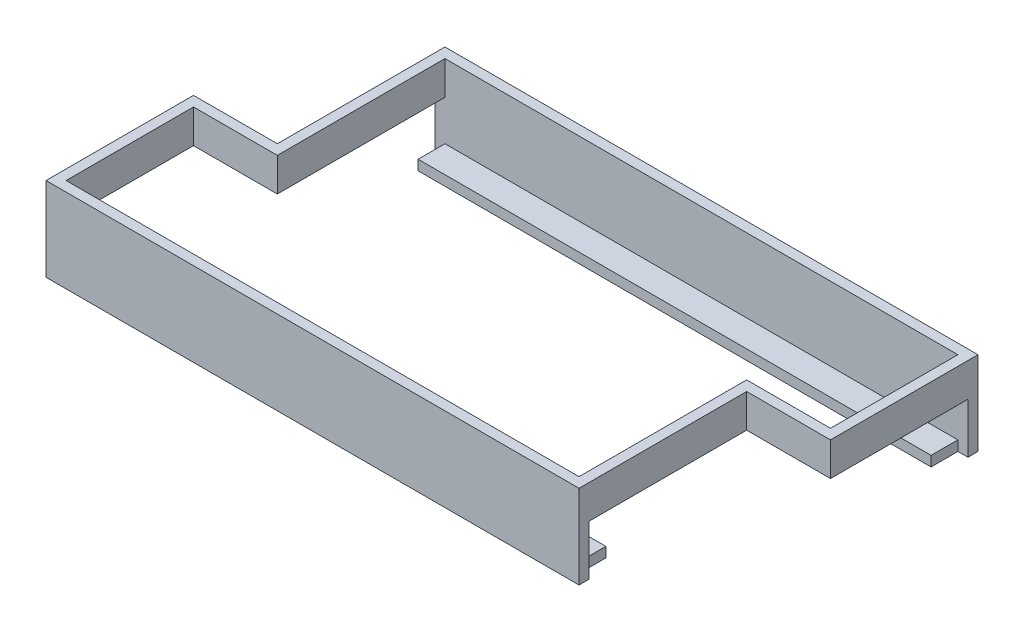
SolidWorks part; units mm, degrees
ref_plane "Front Plane" through (0, 0, 0) normal (0, 0, 1) x (1, 0, 0)
ref_plane "Top Plane" through (0, 0, 0) normal (0, 1, 0) x (1, 0, 0)
ref_plane "Right Plane" through (0, 0, 0) normal (1, 0, 0) x (0, 0, -1)
sketch "Sketch1" plane through (0, 0, 0) normal (0, 1, 0) x (1, 0, 0)
  line L0 (-92, -3) -> (-92, -47)
  line L1 (-67, -47) -> (67, -47)
  line L3 (-67, 47) -> (92, 47)
  line L4 (92, 3) -> (92, 47)
  line L5 (-67, -34.2283) -> (92, 47) construction
  line L6 (-67, 34.2283) -> (67, -34.2283) construction
  line L11 (92, 3) -> (67, 3)
  line L14 (67, 3) -> (67, -47)
  line L15 (-92, -47) -> (-67, -47)
  line L18 (-67, 47) -> (-67, -3)
  line L19 (-67, -3) -> (-92, -3)
  point P0 (0, 0)
  dimension "D2" = 50
  dimension "D3" = 50
  dimension "D4" = 25
  dimension "D5" = 25
extrude "Boss-Extrude1" add sketch "Sketch1" along normal blind 3
sketch "Sketch2" plane through (0, 3, 0) normal (0, 1, 0) x (1, 0, 0)
  line L14 (-64, 44) -> (-64, -6)
  line L15 (-64, -6) -> (-89, -6)
  line L16 (-89, -6) -> (-89, -44)
  line L17 (-89, -44) -> (64, -44)
  line L18 (64, -44) -> (64, 6)
  line L19 (64, 6) -> (89, 6)
  line L20 (89, 6) -> (89, 44)
  line L21 (89, 44) -> (-64, 44)
  line L22 (92, 3) -> (92, 47)
  line L23 (92, 47) -> (-67, 47)
  line L24 (-67, 47) -> (-67, -3)
  line L25 (-67, -3) -> (-92, -3)
  line L26 (-92, -3) -> (-92, -47)
  line L27 (-92, -47) -> (67, -47)
  line L28 (67, -47) -> (67, 3)
  line L29 (67, 3) -> (92, 3)
  line L30 (92, 3) -> (92, 47)
  line L31 (92, 47) -> (-67, 47)
  line L32 (-67, 47) -> (-67, -3)
  line L33 (-67, -3) -> (-92, -3)
  line L34 (-92, -3) -> (-92, -47)
  line L35 (-92, -47) -> (67, -47)
  line L36 (67, -47) -> (67, 3)
  line L37 (67, 3) -> (92, 3)
  dimension "D1" = 0
  dimension "D2" = 3
  dimension "D3" = 3
  dimension "D4" = 3
  dimension "D5" = 3
  dimension "D6" = 3
  dimension "D7" = 3
  dimension "D8" = 3
  dimension "D9" = 3
extrude "Boss-Extrude2" add sketch "Sketch2" along normal blind 22
sketch "Sketch3" plane through (92, 0, 0) normal (1, 0, 0) x (0, 0, -1)
  line L1 (44, 15) -> (-44, 15)
  line L2 (44, 15) -> (44, -4.1918)
  line L3 (44, -4.1918) -> (-44, -4.1918)
  line L4 (-44, 15) -> (-44, -4.1918)
  line L5 (-47, 25) -> (-47, 0) construction
  line L6 (47, 25) -> (47, 0) construction
  dimension "D1" = 3
  dimension "D2" = 3
extrude "Cut-Extrude1" cut sketch "Sketch3" against normal blind 208 contours L3 L4 L1 L2
sketch "Sketch5" plane through (0, 0, 0) normal (0, -1, 0) x (1, 0, 0)
  line L0 (64, 44) -> (64, -6) construction
  line L1 (-89, 44) -> (64, 44)
  line L2 (-89, 44) -> (-89, 36)
  line L3 (-89, 36) -> (64, 36)
  line L4 (64, 44) -> (64, 36)
  line L5 (89, -6) -> (89, -44) construction
  line L6 (-64, -44) -> (89, -44)
  line L7 (-64, -44) -> (-64, -36)
  line L8 (-64, -36) -> (89, -36)
  line L9 (89, -44) -> (89, -36)
  dimension "D1" = 8
  dimension "D2" = 8
extrude "Boss-Extrude3" add sketch "Sketch5" against normal blind 3
